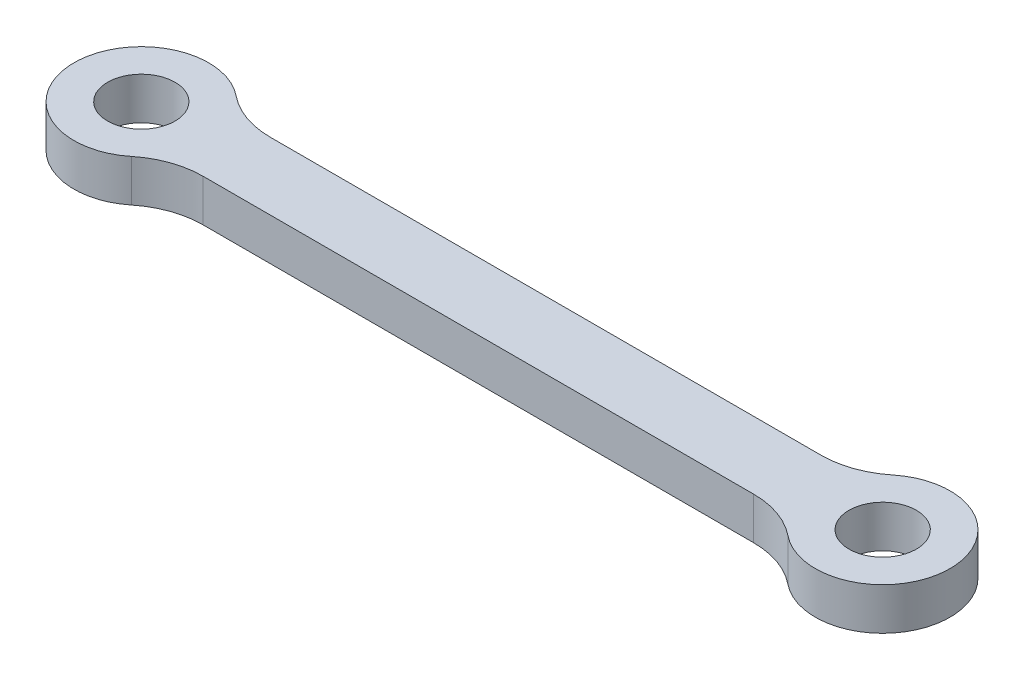
SolidWorks part; units mm, degrees
ref_plane "Front Plane" through (0, 0, 0) normal (0, 0, 1) x (1, 0, 0)
ref_plane "Top Plane" through (0, 0, 0) normal (0, 1, 0) x (1, 0, 0)
ref_plane "Right Plane" through (0, 0, 0) normal (1, 0, 0) x (0, 0, -1)
sketch "Sketch1" plane through (0, 0, 0) normal (0, 1, 0) x (1, 0, 0)
  line L0 (0, 0) -> (0, 4) construction
  line L1 (0, 0) -> (-44, 0) construction
  line L3 (37.0718, -4) -> (-37.0718, -4)
  line L5 (37.0718, 4) -> (-37.0718, 4)
  circle A0 centre (-44, 0) radius 4
  arc A1 (-37.0718, 4) -> (-37.0718, -4) centre (-44, 0) ccw
  arc A2 (37.0718, 4) -> (37.0718, -4) centre (44, 0) cw
  circle A3 centre (44, 0) radius 4
  point P6 (-22, 0)
  point P15 (22, 0)
  dimension "D1" = 8
  dimension "D2" = 16
  dimension "D3" = 44
  dimension "D4" = 8
extrude "Boss-Extrude1" add sketch "Sketch1" along normal blind 5
fillet "Fillet1" radius 10 4 edges at (37.0718, 2.5, 4) (37.0718, 2.5, -4) (-37.0718, 2.5, -4) (-37.0718, 2.5, 4)
